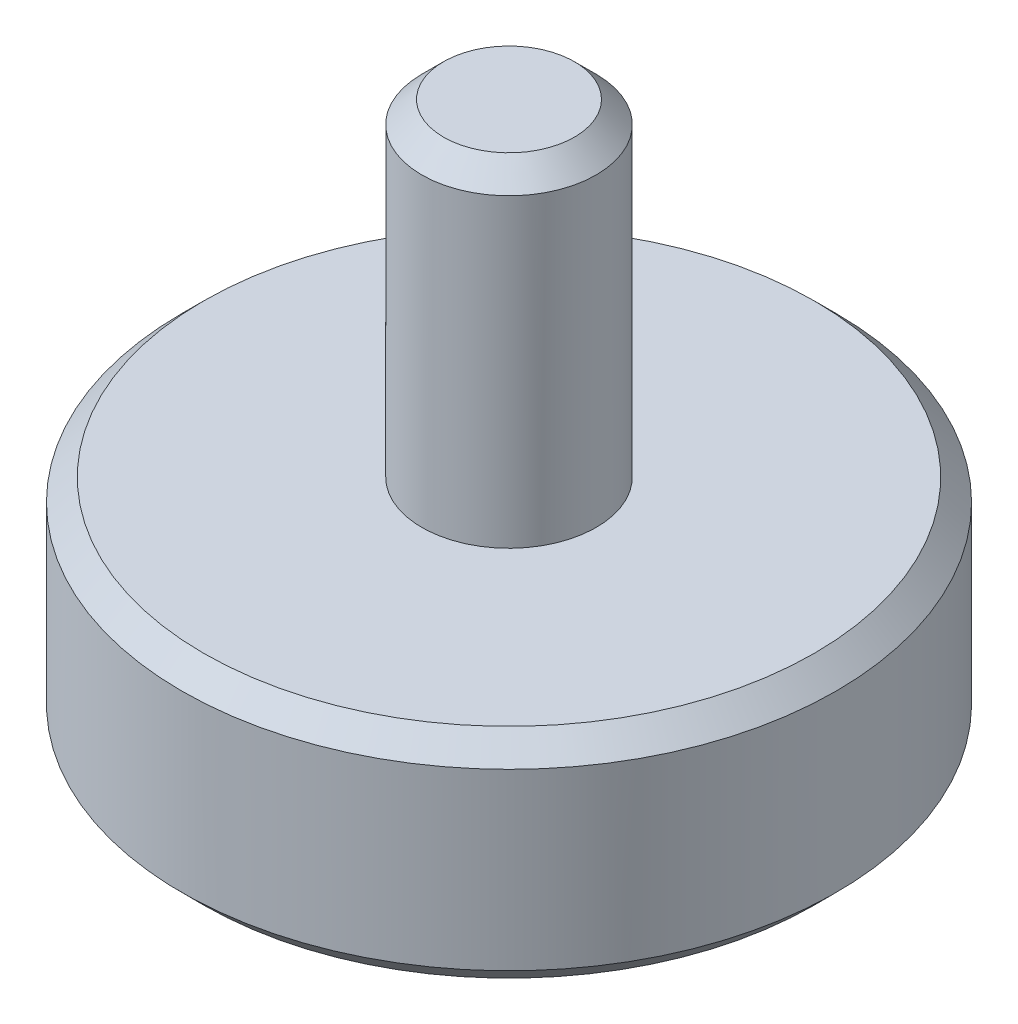
SolidWorks part; units mm, degrees
ref_plane "Спереди" through (0, 0, 0) normal (0, 0, 1) x (1, 0, 0)
ref_plane "Сверху" through (0, 0, 0) normal (0, 1, 0) x (1, 0, 0)
ref_plane "Справа" through (0, 0, 0) normal (1, 0, 0) x (0, 0, -1)
sketch "Эскиз1" plane through (0, 0, 0) normal (0, 0, 1) x (1, 0, 0)
  line L0 (0, 25) -> (4, 25)
  line L1 (4, 25) -> (4, 10)
  line L2 (4, 10) -> (15, 10)
  line L3 (15, 10) -> (15, 0)
  line L4 (15, 0) -> (0, 0)
  line L5 (0, 0) -> (0, 25) construction
  line L6 (0, 25) -> (0, 0)
  point P5 (9.5, 10)
  point P8 (7.5, 0)
  point P9 (15, 5)
  dimension "D1" = 8
  dimension "D2" = 15
  dimension "10" = 10
  dimension "D4" = 30
revolve "Повернуть1" add sketch "Эскиз1" angle 360 about L5
chamfer "Фаска1" distance 1 angle 45 3 edges at (0, 0, -15) (0, 10, -15) (0, 25, -4)
